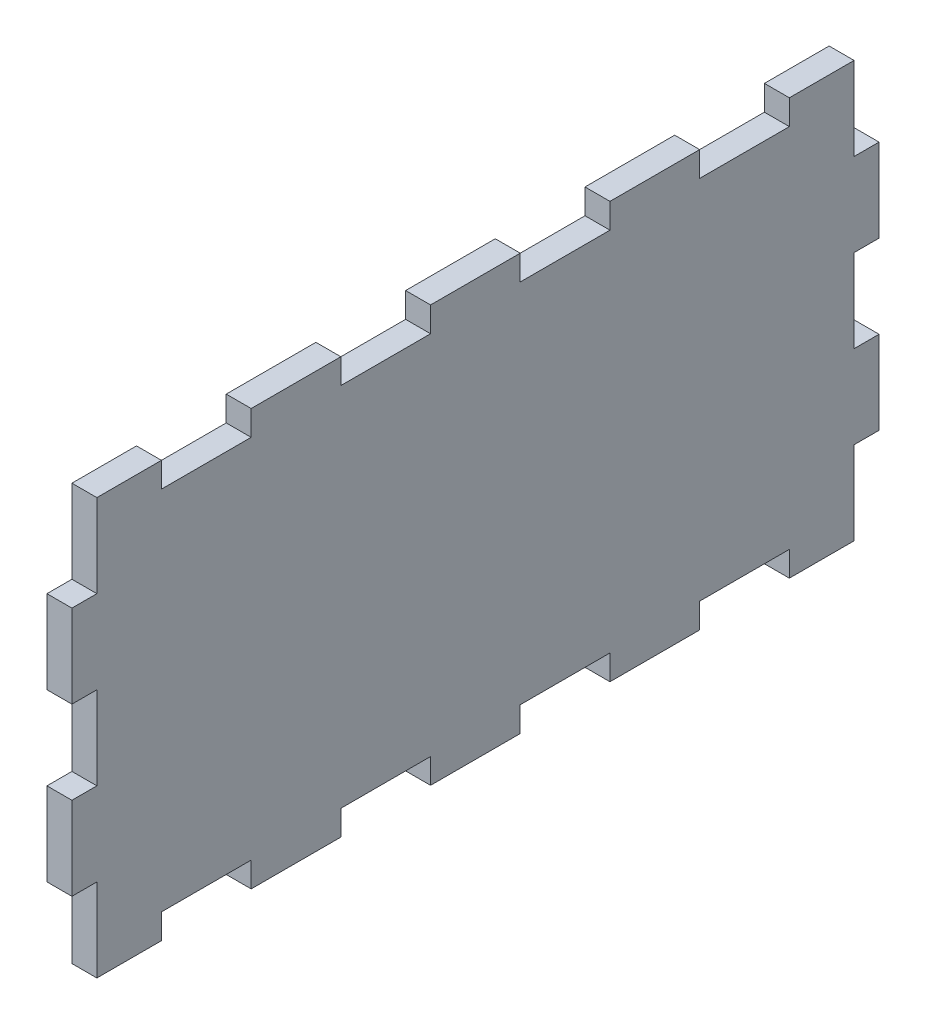
SolidWorks part; units mm, degrees
material "Balsa"
ref_plane "Front" through (0, 0, 0) normal (0, 0, 1) x (1, 0, 0)
ref_plane "Top" through (0, 0, 0) normal (0, 1, 0) x (1, 0, 0)
ref_plane "Right" through (0, 0, 0) normal (1, 0, 0) x (0, 0, -1)
sketch "Esboço1" plane through (0, 0, 0) normal (1, 0, 0) x (0, 0, -1)
  line L1 (48.5, -25) -> (-48.5, -25)
  line L2 (48.5, -25) -> (48.5, 25)
  line L3 (48.5, 25) -> (-48.5, 25)
  line L4 (-48.5, -25) -> (-48.5, 25)
  line L5 (48.5, -25) -> (-48.5, 25) construction
  line L6 (48.5, 25) -> (-48.5, -25) construction
  point P0 (0, 0)
  dimension "D1" = 97
  dimension "D2" = 50
extrude "Ressalto-extrusão1" add sketch "Esboço1" along normal blind 3
sketch "Esboço2" plane through (0, 0, 0) normal (-1, 0, 0) x (0, 0, 1)
  line L0 (-5.38, 22) -> (-16.1622, 22)
  line L1 (-26.94, 22) -> (-37.7222, 22)
  line L2 (-16.1622, 25) -> (-5.38, 25)
  line L3 (5.3978, 25) -> (16.18, 25)
  line L4 (-37.7222, 25) -> (-37.7222, 22)
  line L5 (-26.94, 25) -> (-26.94, 22)
  line L6 (16.18, 22) -> (5.3978, 22)
  line L7 (-16.1622, 25) -> (-16.1622, 22)
  line L8 (26.9578, 25) -> (37.74, 25)
  line L9 (-5.38, 25) -> (-5.38, 22)
  line L10 (-37.7222, -25) -> (-26.94, -25)
  line L11 (5.3978, 25) -> (5.3978, 22)
  line L12 (37.74, -22) -> (26.9578, -22)
  line L13 (16.18, 25) -> (16.18, 22)
  line L14 (-16.1622, -25) -> (-5.38, -25)
  line L15 (26.9578, 25) -> (26.9578, 22)
  line L16 (-26.94, -22) -> (-37.7222, -22)
  line L17 (37.74, 25) -> (37.74, 22)
  line L18 (5.3978, -25) -> (16.18, -25)
  line L19 (-5.38, -22) -> (-16.1622, -22)
  line L20 (26.9578, -25) -> (37.74, -25)
  line L21 (-26.94, -22) -> (-26.94, -25)
  line L22 (16.18, -22) -> (5.3978, -22)
  line L23 (-16.1622, -22) -> (-16.1622, -25)
  line L25 (-5.38, -22) -> (-5.38, -25)
  line L27 (5.3978, -22) -> (5.3978, -25)
  line L29 (16.18, -22) -> (16.18, -25)
  line L31 (26.9578, -22) -> (26.9578, -25)
  line L33 (37.74, -22) -> (37.74, -25)
  line L39 (-37.7222, -22) -> (-37.7222, -25)
  line L40 (-37.7222, 25) -> (-26.94, 25)
  line L41 (37.74, 22) -> (26.9578, 22)
  line L43 (48.5178, 25) -> (48.5178, 22) [skipped]
  line L44 (48.5178, -22) -> (48.5178, -25) [skipped]
  dimension "D1" = 3
  dimension "D3" = 5
  dimension "D4" = 2
extrude "Corte-extrusão1" cut sketch "Esboço2" against normal up to next
sketch "Esboço3" plane through (0, 0, 0) normal (1, 0, 0) x (0, 0, -1)
  line L1 (48.5, -25) -> (-48.5, -25)
  line L2 (48.5, -25) -> (48.5, 25)
  line L3 (48.5, 25) -> (-48.5, 25)
  line L4 (-48.5, -25) -> (-48.5, 25)
  line L5 (48.5, -25) -> (-48.5, 25) construction
  line L6 (48.5, 25) -> (-48.5, -25) construction
  point P0 (0, 0)
  dimension "D1" = 97
  dimension "D2" = 50
sketch "Esboço4" plane through (0, 0, 0) normal (-1, 0, 0) x (0, 0, 1)
  line L0 (45.5, 25) -> (45.5, 15)
  line L1 (45.5, -15) -> (45.5, -25)
  line L2 (-45.5, -5) -> (-45.5, 5)
  line L3 (-48.5, 15) -> (-45.5, 15)
  line L4 (48.5, 15) -> (48.5, 25)
  line L5 (-48.5, 25) -> (48.5, 25) construction
  line L6 (45.5, 15) -> (48.5, 15)
  line L7 (-48.5, -25) -> (48.5, -25) construction
  line L8 (45.5, 5) -> (48.5, 5)
  line L9 (45.5, -25) -> (48.5, -25)
  line L10 (45.5, -5) -> (48.5, -5)
  line L11 (48.5, -25) -> (48.5, -15)
  line L12 (45.5, -15) -> (48.5, -15)
  line L14 (48.5, 25) -> (45.5, 25)
  line L15 (-48.5, 25) -> (-48.5, 15)
  line L16 (-48.5, 5) -> (-45.5, 5)
  line L17 (-48.5, -25) -> (-45.5, -25)
  line L18 (-48.5, -5) -> (-45.5, -5)
  line L19 (-45.5, -25) -> (-45.5, -15)
  line L20 (-48.5, -15) -> (-45.5, -15)
  line L21 (-45.5, 25) -> (-48.5, 25)
  line L22 (-48.5, 5) -> (-48.5, -5)
  line L23 (-45.5, 15) -> (-45.5, 25)
  line L24 (48.5, -5) -> (48.5, 5)
  line L25 (-48.5, -15) -> (-48.5, -25)
  line L26 (45.5, 5) -> (45.5, -5)
  line L29 (-48.5, -25) -> (-45.5, -25) [skipped]
  line L30 (45.5, -25) -> (48.5, -25) [skipped]
  dimension "D1" = 3
  dimension "D3" = 2
  dimension "D4" = 3
extrude "Corte-extrusão2" cut sketch "Esboço4" against normal up to next
